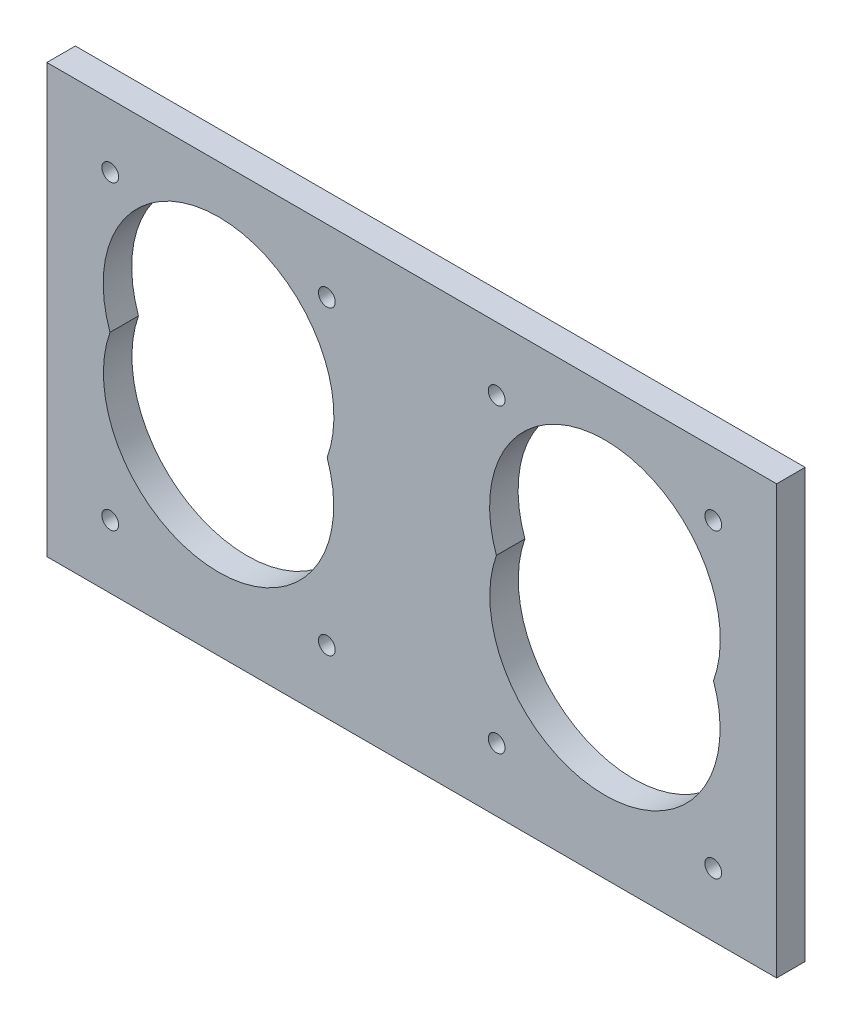
SolidWorks part; units mm, degrees
ref_plane "Front Plane" through (0, 0, 0) normal (0, 0, 1) x (1, 0, 0)
ref_plane "Top Plane" through (0, 0, 0) normal (0, 1, 0) x (1, 0, 0)
ref_plane "Right Plane" through (0, 0, 0) normal (1, 0, 0) x (0, 0, -1)
sketch "Sketch1" plane through (0, 0, 0) normal (0, 0, 1) x (1, 0, 0)
  line L0 (-27, 37) -> (18, 37) construction
  line L1 (-34.62, -30.465) -> (93.4045, -30.465)
  line L2 (-34.62, -30.465) -> (-34.62, 44.62)
  line L3 (-34.62, 44.62) -> (93.4045, 44.62)
  line L4 (93.4045, -30.465) -> (93.4045, 44.62)
  line L6 (18, -22.845) -> (-27, -22.845) construction
  line L7 (29.3923, 47.4436) -> (29.3923, -48.0943) construction
  line L8 (-1.522, 35.265) -> (0.428, 34.861) construction
  line L9 (-22.495, 23.506) -> (-23.167, 21.631) construction
  line L10 (14.167, 21.631) -> (14.645, 19.697) construction
  line L11 (-20.427, -8.82) -> (-22.01, -6.152) construction
  line L12 (13.01, -6.152) -> (11.427, -8.82) construction
  line L13 (-7.593, -16.823) -> (-4.5, -17.07) construction
  circle A0 centre (-4.5, 15.9942) radius 19.4742
  circle A1 centre (63.2846, 15.9942) radius 19.4742
  circle A2 centre (-4.5, 2.4297) radius 19.4378
  circle A3 centre (63.2845, 2.4297) radius 19.4378
  circle A4 centre (-4.5, 15.9942) radius 20.2362
  circle A5 centre (-4.5, 2.4297) radius 20.1998
  circle A6 centre (63.2845, 2.4297) radius 20.1998
  circle A7 centre (63.2846, 15.9942) radius 20.2362
  dimension "D5" = 0.762
  dimension "D6" = 0.762
  dimension "D1" = 7.62
  dimension "D2" = 7.62
  dimension "D3" = 7.62
  dimension "D4" = 7.62
extrude "Boss-Extrude1" add sketch "Sketch1" along normal blind 5 contours L3 L7 L1 L4 A7 A6 | L7 L3 L2 L1 A5 A4
sketch "Sketch7" plane through (0, 0, 5) normal (0, 0, 1) x (1, 0, 0)
  circle A0 centre (-23.5006, 33.4996) radius 1.4732
  circle A1 centre (14.4994, 33.5003) radius 1.4732
  circle A2 centre (-23.4996, -19.3454) radius 1.4732
  circle A3 centre (14.5004, -19.3447) radius 1.4732
  circle A4 centre (44.2848, -19.3453) radius 1.4732
  circle A5 centre (44.2842, 33.4997) radius 1.4732
  circle A6 centre (82.2842, 33.5002) radius 1.4732
  circle A7 centre (82.2848, -19.3448) radius 1.4732
  circle A8 centre (-23.5006, 33.4996) radius 1.4732 construction
extrude "Cut-Extrude1" cut sketch "Sketch7" against normal blind 10
